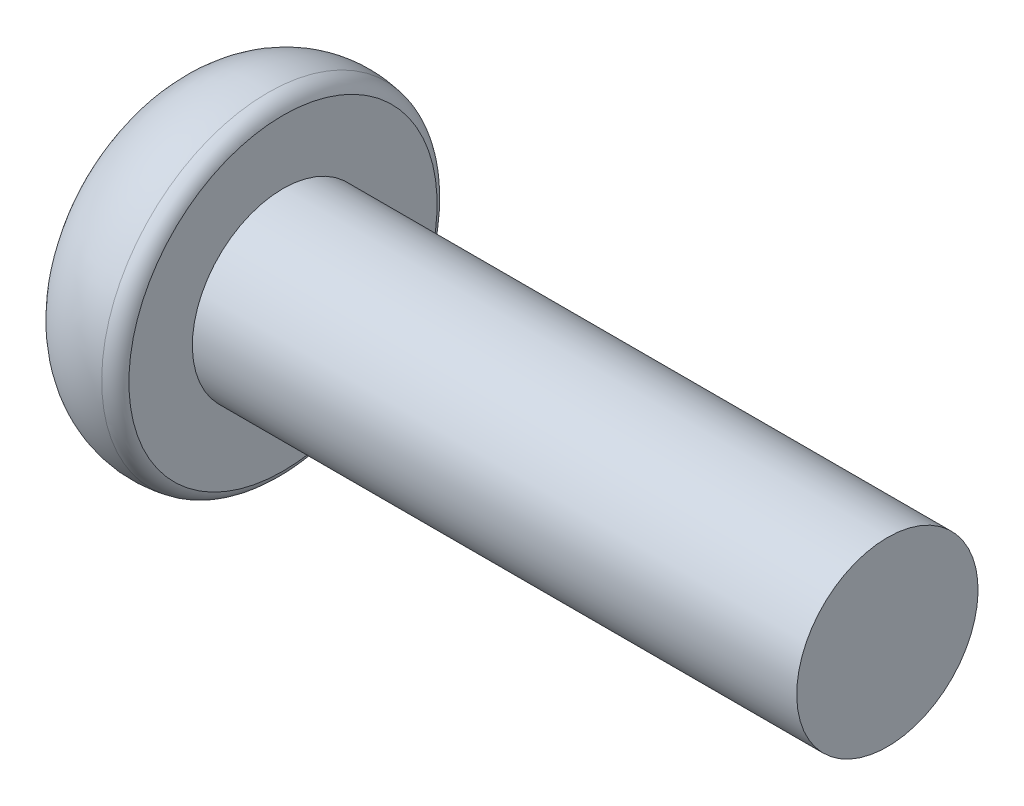
SolidWorks part; units mm, degrees
material "AISI 1020"
ref_plane "Front Plane" through (0, 0, 0) normal (0, 0, 1) x (1, 0, 0)
ref_plane "Top Plane" through (0, 0, 0) normal (0, 1, 0) x (1, 0, 0)
ref_plane "Right Plane" through (0, 0, 0) normal (1, 0, 0) x (0, 0, -1)
sketch "Sketch1" plane through (0, 0, 0) normal (0, 0, 1) x (1, 0, 0)
  line L0 (0, 0) -> (20, 0)
  line L1 (20, 0) -> (20, -3)
  line L2 (20, -3) -> (-4, -3)
  line L5 (0, 2.1) -> (0, 0)
  line L6 (-4, -3) -> (-4, 0)
  line L7 (-0.5, -3) -> (-0.5, 2.5) construction
  arc A1 (-4, 0) -> (-0.5, 2.5) centre (-1.0678, -0.405) cw
  arc A2 (-0.5, 2.5) -> (0, 2.1) centre (-0.567, 1.9038) cw
  dimension "D4" = 0.4
  dimension "D8" = 2.96
  dimension "D9" = 0.6
  dimension "D1" = 3
  dimension "D2" = 4
  dimension "D3" = 5.5
  dimension "D5" = 20
  dimension "D6" = 0.5
  dimension "D7" = 3
revolve "Revolve1" add sketch "Sketch1" angle 360 about L2
cosmetic thread "Cosmetic Thread1" parameters "D2"=2
sketch "Sketch2" plane through (-4, 0, 0) normal (-1, 0, 0) x (0, 0, 1)
  line L1 (0, -0.4597) -> (-2.2, -1.7298)
  line L2 (-2.2, -1.7298) -> (-2.2, -4.2702)
  line L3 (-2.2, -4.2702) -> (0, -5.5403)
  line L4 (0, -5.5403) -> (2.2, -4.2702)
  line L5 (2.2, -4.2702) -> (2.2, -1.7298)
  line L6 (2.2, -1.7298) -> (0, -0.4597)
  circle A0 centre (0, -3) radius 2.2 construction
  dimension "D1" = 4.4
extrude "Cut-Extrude1" cut sketch "Sketch2" against normal blind 3
